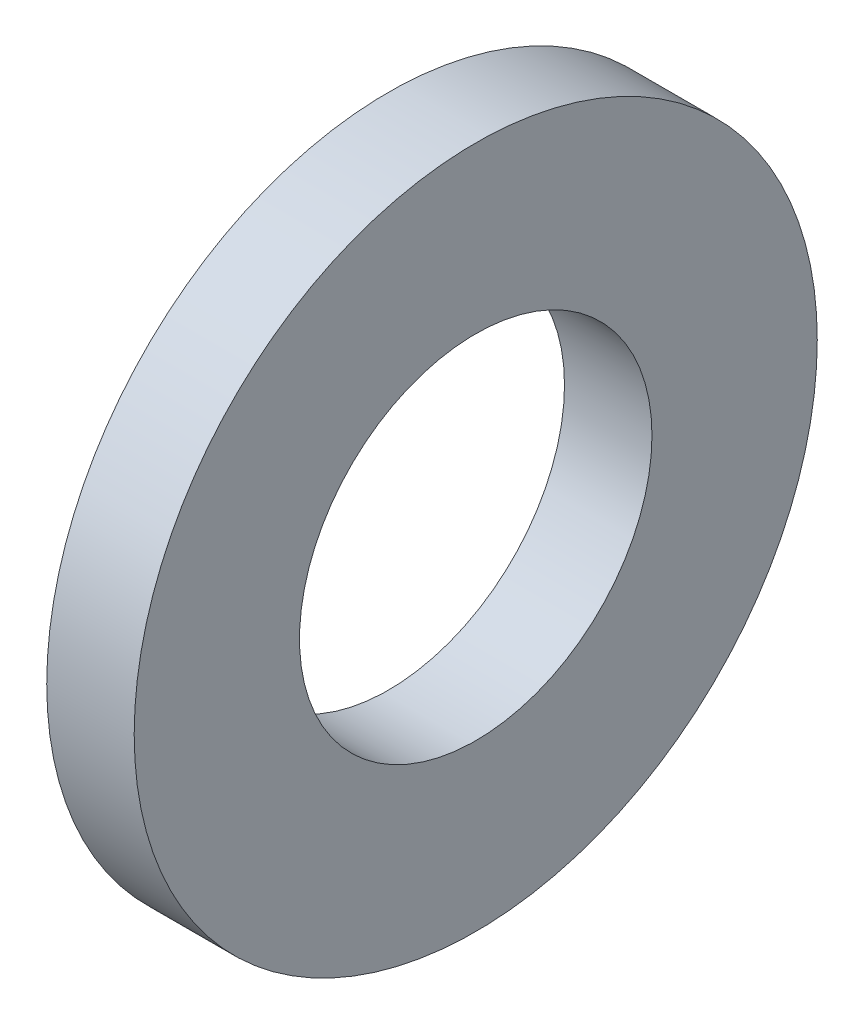
SolidWorks part; units mm, degrees
ref_plane "Plane1" through (0, 0, 0) normal (0, 0, 1) x (1, 0, 0)
ref_plane "Plane2" through (0, 0, 0) normal (0, 1, 0) x (1, 0, 0)
ref_plane "Plane3" through (0, 0, 0) normal (1, 0, 0) x (0, 0, -1)
sketch "Sketch1" plane through (0, 0, 0) normal (1, 0, 0) x (0, 0, -1)
  circle A0 centre (0, 0) radius 2.015
  circle A1 centre (0, 0) radius 3.905
  dimension "OutsideDia" = 7.81
  dimension "InsideDia" = 4.03
extrude "Base-Extrude" add sketch "Sketch1" along normal blind 1
